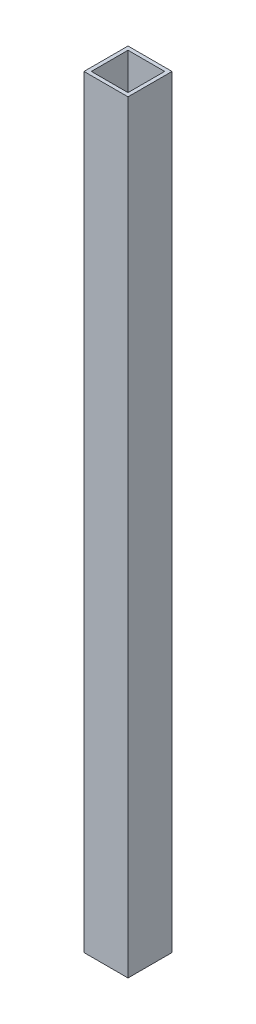
SolidWorks part; units mm, degrees
ref_plane "Front" through (0, 0, 0) normal (0, 0, 1) x (1, 0, 0)
ref_plane "Top" through (0, 0, 0) normal (0, 1, 0) x (1, 0, 0)
ref_plane "Right" through (0, 0, 0) normal (1, 0, 0) x (0, 0, -1)
sketch "Sketch1" plane through (0, 0, 0) normal (0, 1, 0) x (1, 0, 0)
  line L1 (0, 0) -> (19.05, 0)
  line L2 (0, 0) -> (0, 19.05)
  line L3 (0, 19.05) -> (19.05, 19.05)
  line L4 (19.05, 0) -> (19.05, 19.05)
  line L5 (0, 0) -> (19.05, 19.05) construction
  line L6 (0, 19.05) -> (19.05, 0) construction
  line L7 (1.5875, 1.5875) -> (17.4625, 1.5875)
  line L8 (1.5875, 1.5875) -> (1.5875, 17.4625)
  line L9 (1.5875, 17.4625) -> (17.4625, 17.4625)
  line L10 (17.4625, 1.5875) -> (17.4625, 17.4625)
  line L11 (1.5875, 1.5875) -> (17.4625, 17.4625) construction
  line L12 (1.5875, 17.4625) -> (17.4625, 1.5875) construction
  point P4 (9.525, 9.525)
  point P5 (9.525, 9.525)
  dimension "D1" = 1.5875
  dimension "D2" = 1.5875
  dimension "D3" = 19.05
extrude "Boss-Extrude1" add sketch "Sketch1" along normal blind 330.2
